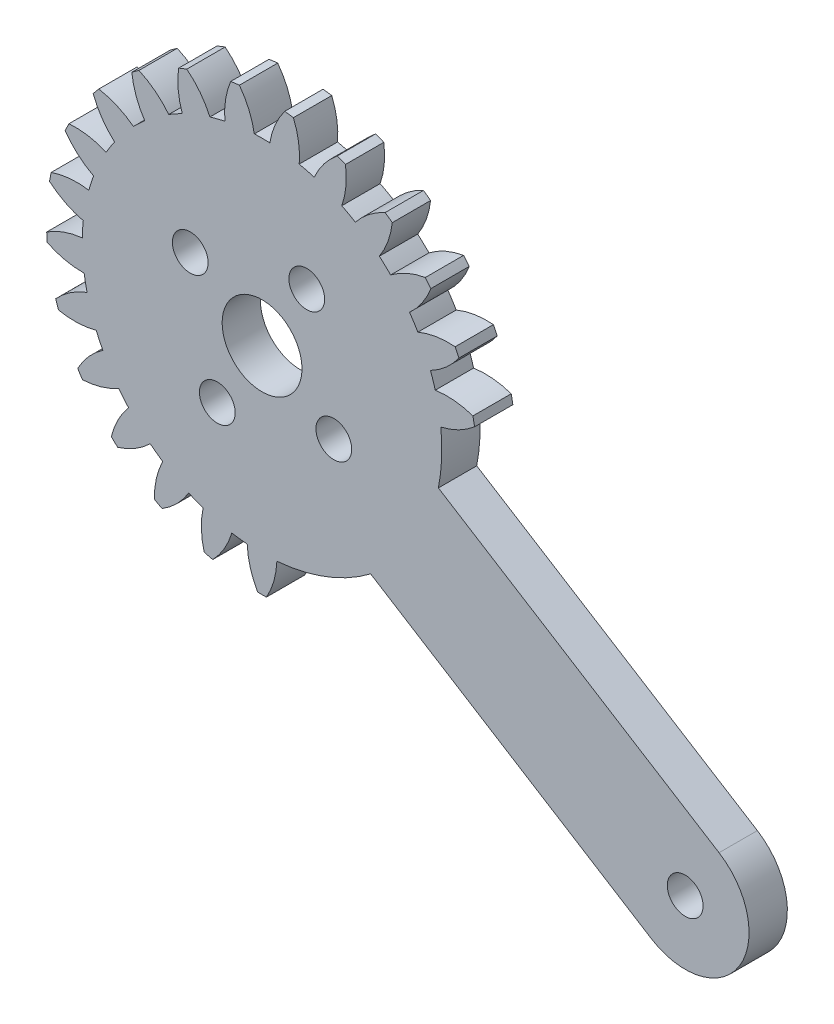
SolidWorks part; units mm, degrees
ref_plane "Front Plane" through (0, 0, 0) normal (0, 0, 1) x (1, 0, 0)
ref_plane "Top Plane" through (0, 0, 0) normal (0, 1, 0) x (1, 0, 0)
ref_plane "Right Plane" through (0, 0, 0) normal (1, 0, 0) x (0, 0, -1)
sketch "Model" plane through (0, 0, 0) normal (0, 0, 1) x (1, 0, 0)
  line L0 (0, 14.3002) -> (0, 3.175)
  line L1 (0, -3.175) -> (1.1795, -14.2515)
  circle A0 centre (0, 0) radius 3.175
  arc A1 (6.6358, 15.8088) -> (5.9846, 16.0666) centre (0, 0) ccw
  arc A2 (6.343, 12.8165) -> (6.6358, 15.8088) centre (0.3492, 14.9135) ccw
  arc A3 (7.4226, 12.223) -> (6.343, 12.8165) centre (0, 0) ccw
  arc A4 (9.7922, 14.0735) -> (7.4226, 12.223) centre (12.4048, 8.2859) ccw
  arc A5 (10.3588, 13.6619) -> (9.7922, 14.0735) centre (0, 0) ccw
  arc A6 (9.331, 10.8364) -> (10.3588, 13.6619) centre (4.0471, 14.3582) ccw
  arc A7 (10.2291, 9.993) -> (9.331, 10.8364) centre (0, 0) ccw
  arc A8 (12.9845, 11.1962) -> (10.2291, 9.993) centre (14.0757, 4.9407) ccw
  arc A9 (13.4309, 10.6565) -> (12.9845, 11.1962) centre (0, 0) ccw
  arc A10 (11.7328, 8.1754) -> (13.4309, 10.6565) centre (7.4907, 12.9006) ccw
  arc A11 (12.3929, 7.1352) -> (11.7328, 8.1754) centre (0, 0) ccw
  arc A12 (15.3609, 7.6153) -> (12.3929, 7.1352) centre (14.8622, 1.2849) ccw
  arc A13 (15.6591, 6.9816) -> (15.3609, 7.6153) centre (0, 0) ccw
  arc A14 (13.3973, 5.0008) -> (15.6591, 6.9816) centre (10.4636, 10.6324) ccw
  arc A15 (13.778, 3.829) -> (13.3973, 5.0008) centre (0, 0) ccw
  arc A16 (16.7722, 3.556) -> (13.778, 3.829) centre (14.7148, -2.4515) ccw
  arc A17 (16.9034, 2.868) -> (16.7722, 3.556) centre (0, 0) ccw
  arc A18 (14.2201, 1.5119) -> (16.9034, 2.868) centre (12.779, 7.6962) ccw
  arc A19 (14.2974, 0.2823) -> (14.2201, 1.5119) centre (0, 0) ccw
  arc A20 (17.1296, -0.7268) -> (14.2974, 0.2823) centre (13.6429, -6.0339) ccw
  arc A21 (17.0856, -1.4258) -> (17.1296, -0.7268) centre (0, 0) ccw
  arc A22 (14.1493, -2.072) -> (17.0856, -1.4258) centre (14.2915, 4.2764) ccw
  arc A23 (13.9184, -3.2822) -> (14.1493, -2.072) centre (0, 0) ccw
  arc A24 (16.4107, -4.9639) -> (13.9184, -3.2822) centre (11.7137, -9.2372) ccw
  arc A25 (16.1942, -5.63) -> (16.4107, -4.9639) centre (0, 0) ccw
  arc A26 (13.1895, -5.5257) -> (16.1942, -5.63) centre (14.906, 0.5879) ccw
  arc A27 (12.6649, -6.6405) -> (13.1895, -5.5257) centre (0, 0) ccw
  arc A28 (14.6606, -8.8892) -> (12.6649, -6.6405) centre (9.0485, -11.86) ccw
  arc A29 (14.2853, -9.4805) -> (14.6606, -8.8892) centre (0, 0) ccw
  arc A30 (11.4009, -8.6322) -> (14.2853, -9.4805) centre (14.5839, -3.1375) ccw
  arc A31 (10.6156, -9.5815) -> (11.4009, -8.6322) centre (0, 0) ccw
  arc A32 (11.9894, -12.2558) -> (10.6156, -9.5815) centre (5.8147, -13.7377) ccw
  arc A33 (11.4788, -12.7353) -> (11.9894, -12.2558) centre (0, 0) ccw
  arc A34 (8.896, -11.1963) -> (11.4788, -12.7353) centre (13.3455, -6.6658) ccw
  arc A35 (7.8993, -11.9205) -> (8.896, -11.1963) centre (0, 0) ccw
  arc A36 (8.5648, -14.8524) -> (7.8993, -11.9205) centre (2.2156, -14.7522) ccw
  arc A37 (7.9511, -15.1899) -> (8.5648, -14.8524) centre (0, 0) ccw
  arc A38 (5.8321, -13.0569) -> (7.9511, -15.1899) centre (11.2685, -9.7753) ccw
  arc A39 (4.6866, -13.5104) -> (5.8321, -13.0569) centre (0, 0) ccw
  arc A40 (4.6021, -16.5158) -> (4.6866, -13.5104) centre (-1.5227, -14.8397) ccw
  arc A41 (3.9237, -16.69) -> (4.6021, -16.5158) centre (0, 0) ccw
  arc A42 (2.4018, -14.0971) -> (3.9237, -16.69) centre (8.4834, -12.2706) ccw
  arc A43 (1.1795, -14.2515) -> (2.4018, -14.0971) centre (0, 0) ccw
  arc A44 (0.3502, -17.1414) -> (1.1795, -14.2515) centre (-5.1654, -13.9948) ccw
  arc A45 (-0.3502, -17.1414) -> (0.3502, -17.1414) centre (0, 0) ccw
  arc A46 (-1.1795, -14.2515) -> (-0.3502, -17.1414) centre (5.1654, -13.9948) ccw
  arc A47 (-2.4018, -14.0971) -> (-1.1795, -14.2515) centre (0, 0) ccw
  arc A48 (-3.9237, -16.69) -> (-2.4018, -14.0971) centre (-8.4834, -12.2706) ccw
  arc A49 (-4.6021, -16.5158) -> (-3.9237, -16.69) centre (0, 0) ccw
  arc A50 (-4.6866, -13.5104) -> (-4.6021, -16.5158) centre (1.5227, -14.8397) ccw
  arc A51 (-5.8321, -13.0569) -> (-4.6866, -13.5104) centre (0, 0) ccw
  arc A52 (-7.9511, -15.1899) -> (-5.8321, -13.0569) centre (-11.2685, -9.7753) ccw
  arc A53 (-8.5648, -14.8524) -> (-7.9511, -15.1899) centre (0, 0) ccw
  arc A54 (-7.8993, -11.9205) -> (-8.5648, -14.8524) centre (-2.2156, -14.7522) ccw
  arc A55 (-8.896, -11.1963) -> (-7.8993, -11.9205) centre (0, 0) ccw
  arc A56 (-11.4788, -12.7353) -> (-8.896, -11.1963) centre (-13.3455, -6.6658) ccw
  arc A57 (-11.9894, -12.2558) -> (-11.4788, -12.7353) centre (0, 0) ccw
  arc A58 (-10.6156, -9.5815) -> (-11.9894, -12.2558) centre (-5.8147, -13.7377) ccw
  arc A59 (-11.4009, -8.6322) -> (-10.6156, -9.5815) centre (0, 0) ccw
  arc A60 (-14.2853, -9.4805) -> (-11.4009, -8.6322) centre (-14.5839, -3.1375) ccw
  arc A61 (-14.6606, -8.8892) -> (-14.2853, -9.4805) centre (0, 0) ccw
  arc A62 (-12.6649, -6.6405) -> (-14.6606, -8.8892) centre (-9.0485, -11.86) ccw
  arc A63 (-13.1895, -5.5257) -> (-12.6649, -6.6405) centre (0, 0) ccw
  arc A64 (-16.1942, -5.63) -> (-13.1895, -5.5257) centre (-14.906, 0.5879) ccw
  arc A65 (-16.4107, -4.9639) -> (-16.1942, -5.63) centre (0, 0) ccw
  arc A66 (-13.9184, -3.2822) -> (-16.4107, -4.9639) centre (-11.7137, -9.2372) ccw
  arc A67 (-14.1493, -2.072) -> (-13.9184, -3.2822) centre (0, 0) ccw
  arc A68 (-17.0856, -1.4258) -> (-14.1493, -2.072) centre (-14.2915, 4.2764) ccw
  arc A69 (-17.1296, -0.7268) -> (-17.0856, -1.4258) centre (0, 0) ccw
  arc A70 (-14.2974, 0.2823) -> (-17.1296, -0.7268) centre (-13.6429, -6.0339) ccw
  arc A71 (-14.2201, 1.5119) -> (-14.2974, 0.2823) centre (0, 0) ccw
  arc A72 (-16.9034, 2.868) -> (-14.2201, 1.5119) centre (-12.779, 7.6962) ccw
  arc A73 (-16.7722, 3.556) -> (-16.9034, 2.868) centre (0, 0) ccw
  arc A74 (-13.778, 3.829) -> (-16.7722, 3.556) centre (-14.7148, -2.4515) ccw
  arc A75 (-13.3973, 5.0008) -> (-13.778, 3.829) centre (0, 0) ccw
  arc A76 (-15.6591, 6.9816) -> (-13.3973, 5.0008) centre (-10.4636, 10.6324) ccw
  arc A77 (-15.3609, 7.6153) -> (-15.6591, 6.9816) centre (0, 0) ccw
  arc A78 (-12.3929, 7.1352) -> (-15.3609, 7.6153) centre (-14.8622, 1.2849) ccw
  arc A79 (-11.7328, 8.1754) -> (-12.3929, 7.1352) centre (0, 0) ccw
  arc A80 (-13.4309, 10.6565) -> (-11.7328, 8.1754) centre (-7.4907, 12.9006) ccw
  arc A81 (-12.9845, 11.1962) -> (-13.4309, 10.6565) centre (0, 0) ccw
  arc A82 (-10.2291, 9.993) -> (-12.9845, 11.1962) centre (-14.0757, 4.9407) ccw
  arc A83 (-9.331, 10.8364) -> (-10.2291, 9.993) centre (0, 0) ccw
  arc A84 (-10.3588, 13.6619) -> (-9.331, 10.8364) centre (-4.0471, 14.3582) ccw
  arc A85 (-9.7922, 14.0735) -> (-10.3588, 13.6619) centre (0, 0) ccw
  arc A86 (-7.4226, 12.223) -> (-9.7922, 14.0735) centre (-12.4048, 8.2859) ccw
  arc A87 (-6.343, 12.8165) -> (-7.4226, 12.223) centre (0, 0) ccw
  arc A88 (-6.6358, 15.8088) -> (-6.343, 12.8165) centre (-0.3492, 14.9135) ccw
  arc A89 (-5.9846, 16.0666) -> (-6.6358, 15.8088) centre (0, 0) ccw
  arc A90 (-4.1497, 13.6849) -> (-5.9846, 16.0666) centre (-9.9545, 11.1105) ccw
  arc A91 (-2.9563, 13.9913) -> (-4.1497, 13.6849) centre (0, 0) ccw
  arc A92 (-2.4958, 16.9624) -> (-2.9563, 13.9913) centre (3.3706, 14.5318) ccw
  arc A93 (-1.801, 17.0501) -> (-2.4958, 16.9624) centre (0, 0) ccw
  arc A94 (-0.616, 14.2869) -> (-1.801, 17.0501) centre (-6.8786, 13.2371) ccw
  arc A95 (0.616, 14.2869) -> (-0.616, 14.2869) centre (0, 0) ccw
  arc A96 (1.801, 17.0501) -> (0.616, 14.2869) centre (6.8786, 13.2371) ccw
  arc A97 (2.4958, 16.9624) -> (1.801, 17.0501) centre (0, 0) ccw
  arc A98 (2.9563, 13.9913) -> (2.4958, 16.9624) centre (-3.3706, 14.5318) ccw
  arc A99 (4.1497, 13.6849) -> (2.9563, 13.9913) centre (0, 0) ccw
  arc A100 (5.9846, 16.0666) -> (4.1497, 13.6849) centre (9.9545, 11.1105) ccw
  arc A101 (0.616, 14.2869) -> (2.4018, -14.0971) centre (0, 0) cw
extrude "Boss-Extrude1" add sketch "Model" along normal blind 3.048 contours L0 A95 A94 A93 A92 A91 A90 A89 A88 A87 A86 A85 A84 A83 A82 A81 A80 A79 A78 A77 A76 A75 A74 A73 A72 A71 A70 A69 A68 A67 A66 A65 A64 A63 A62 A61 A60 A59 A58 A57 A56 A55 A54 A53 A52 A51 A50 A49 A48 A47 A46 | A101 A23 A19 A15 A11 A7 A3 A99 A95 L0 A0 L1 A43 A39 A35 A31 A27 | A96 A101 A98 A97 | A100 A101 A2 A1 | A4 A101 A6 A5 | A8 A101 A10 A9 | A12 A101 A14 A13 | A16 A101 A18 A17
sketch "Sketch2" plane through (0, 0, 0) normal (0, 0, -1) x (-1, 0, 0)
  line L0 (50.8913, -41.8399) -> (-33.6586, -21.0525) construction
  line L1 (6.3195, -40.7883) -> (8.6164, -31.4462) construction
  line L2 (-24.5123, -33.208) -> (37.1514, -48.3687) construction
  line L3 (37.1514, -48.3687) -> (52.312, 13.295) construction
  line L4 (0, 0) -> (-33.6586, -21.0525) construction
  line L5 (2.6939, -4.3069) -> (-30.9647, -25.3594)
  line L6 (-2.6939, 4.3069) -> (-36.3524, -16.7456)
  circle A0 centre (-33.6586, -21.0525) radius 1.4224
  arc A1 (2.6939, -4.3069) -> (-2.6939, 4.3069) centre (0, 0) ccw
  arc A2 (-36.3524, -16.7456) -> (-30.9647, -25.3594) centre (-33.6586, -21.0525) ccw
  arc A3 (-14.2201, 1.5119) -> (-1.1795, -14.2515) centre (0, 0) ccw construction
  arc A4 (-14.2201, 1.5119) -> (-1.1795, -14.2515) centre (0, 0) ccw
  point P11 (-16.8293, -10.5262)
  dimension "D1" = 2.8448
  dimension "D2" = 10.16
extrude "Boss-Extrude2" add sketch "Sketch2" against normal blind 3.048 contours A4 L6 A2 L5 A0
sketch "Sketch3" plane through (0, 0, 3.048) normal (0, 0, 1) x (1, 0, 0)
  line L2 (14.027, -2.7817) -> (36.3524, -16.7456) construction
  circle A0 centre (3.558, 5.6884) radius 1.4224
  circle A1 centre (5.7101, -3.5715) radius 1.4224
  circle A2 centre (-3.558, -5.6884) radius 1.4224
  circle A3 centre (-5.7101, 3.5715) radius 1.4224
  line B0 (-3.6287, 2.2696) -> (3.6287, -2.2696) construction
  line B1 (-5.3073, 3.3196) -> (-4.4341, 2.7734) construction
  line B2 (4.4341, -2.7734) -> (5.3073, -3.3196) construction
  line B3 (-14.3239, 8.9592) -> (-5.7101, 3.5715) construction
  line B4 (5.7101, -3.5715) -> (12.6011, -7.8817) construction
  line B5 (2.2561, 3.607) -> (-2.2561, -3.607) construction
  line B6 (2.7599, 4.4125) -> (3.3061, 5.2857) construction
  line B7 (-2.7599, -4.4125) -> (-3.3061, -5.2857) construction
  circle B8 centre (4.0314, -2.5215) radius 0.475
  circle B9 centre (-4.0314, 2.5215) radius 0.475
  circle B10 centre (5.7101, -3.5715) radius 0.475
  circle B11 centre (-5.7101, 3.5715) radius 0.475
  circle B12 centre (-7.4328, 4.649) radius 0.475
  circle B13 centre (-9.1556, 5.7266) radius 0.475
  circle B14 centre (-10.8784, 6.8041) radius 0.475
  circle B15 centre (-12.6011, 7.8817) radius 0.475
  circle B16 centre (-14.3239, 8.9592) radius 0.475
  circle B17 centre (7.4328, -4.649) radius 0.475
  circle B18 centre (9.1556, -5.7266) radius 0.475
  circle B19 centre (10.8784, -6.8041) radius 0.475
  circle B20 centre (12.6011, -7.8817) radius 0.475
  circle B21 centre (2.508, 4.0098) radius 0.475
  circle B22 centre (-2.508, -4.0098) radius 0.475
  circle B23 centre (3.558, 5.6884) radius 0.475
  circle B24 centre (-3.558, -5.6884) radius 0.475
  dimension "D1" = 2.8448
sketch_block_instance "ServoHoles-1"
sketch_block "ServoHoles" parameters "D2"=0.95, "D1"=8.56, "D3"=12.52, "D4"=2.032, "D5"=2.032, "D6"=8.509
extrude "Cut-Extrude1" cut sketch "Sketch3" against normal through all contours A3 B11 | A0 B23 | B11 | B23 | A1 | A2
